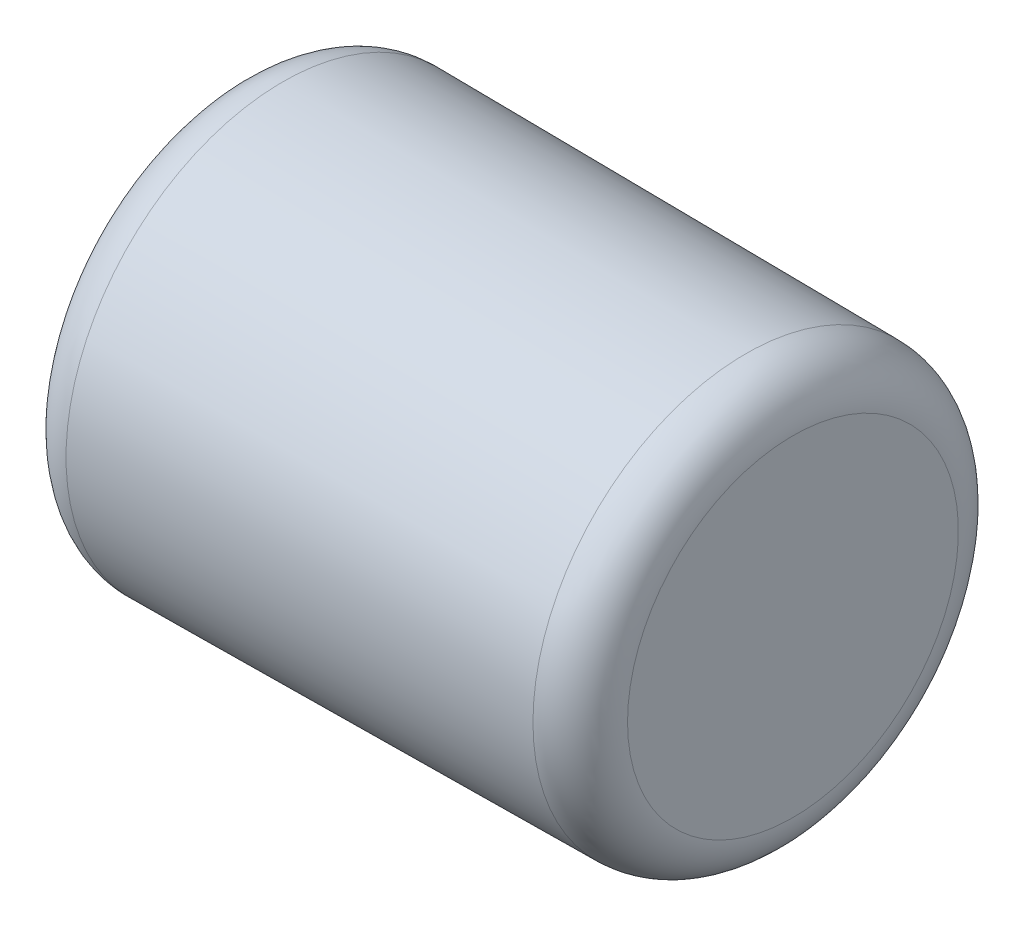
SolidWorks part; units mm, degrees
ref_plane "Front Plane" through (0, 0, 0) normal (0, 0, 1) x (1, 0, 0)
ref_plane "Top Plane" through (0, 0, 0) normal (0, 1, 0) x (1, 0, 0)
ref_plane "Right Plane" through (0, 0, 0) normal (1, 0, 0) x (0, 0, -1)
sketch "Sketch1" plane through (0, 0, 0) normal (0, 0, 1) x (1, 0, 0)
  line L0 (-5.0668, 0) -> (7.9943, 0) construction
  line L1 (0, 0) -> (0, 9.15)
  line L2 (0, 9.15) -> (23.5, 8.95)
  line L3 (23.5, 8.95) -> (23.5, 0)
  line L4 (0, 0) -> (23.5, 0)
  dimension "D1" = 9.15
  dimension "D2" = 8.95
  dimension "D3" = 23.5
revolve "Revolve1" add sketch "Sketch1" angle 360 about L0
fillet "Fillet1" radius 2 2 edges at (23.5, 0, 8.95) (0, 0, 9.15)
